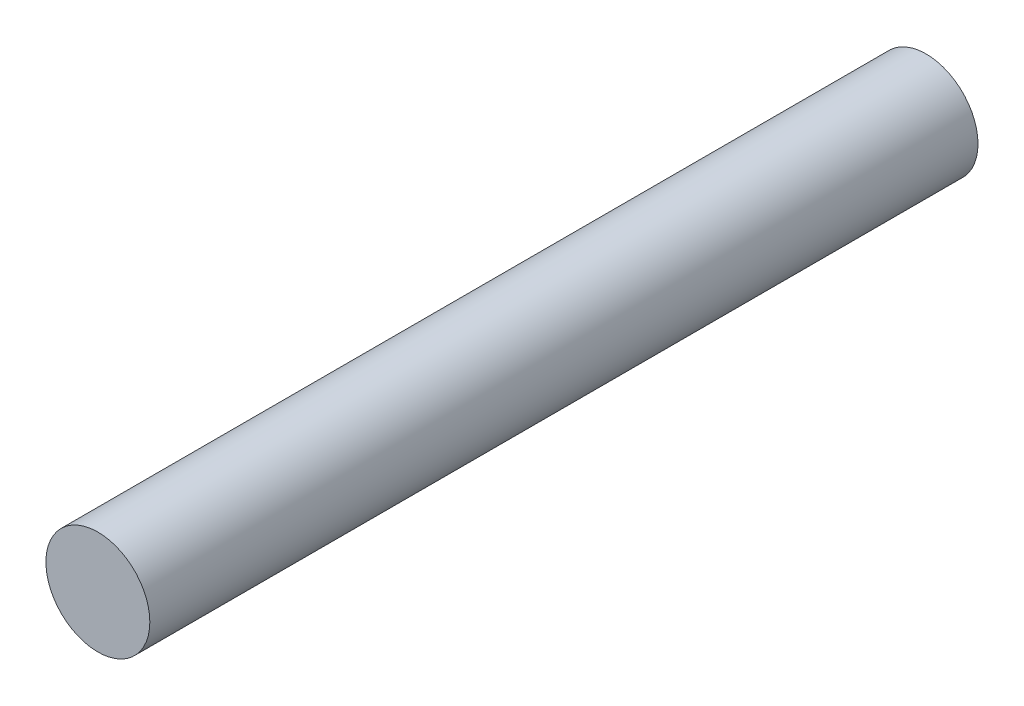
SolidWorks part; units mm, degrees
ref_plane "Plan de face" through (0, 0, 0) normal (0, 0, 1) x (1, 0, 0)
ref_plane "Plan de dessus" through (0, 0, 0) normal (0, 1, 0) x (1, 0, 0)
ref_plane "Plan de droite" through (0, 0, 0) normal (1, 0, 0) x (0, 0, -1)
sketch "Esquisse2" plane through (0, 0, 0) normal (0, 0, 1) x (1, 0, 0)
  circle A0 centre (0, 0) radius 49.403
  dimension "D1" = 98.806
extrude "Boss.-Extru.1" add sketch "Esquisse2" along normal blind 787.4
